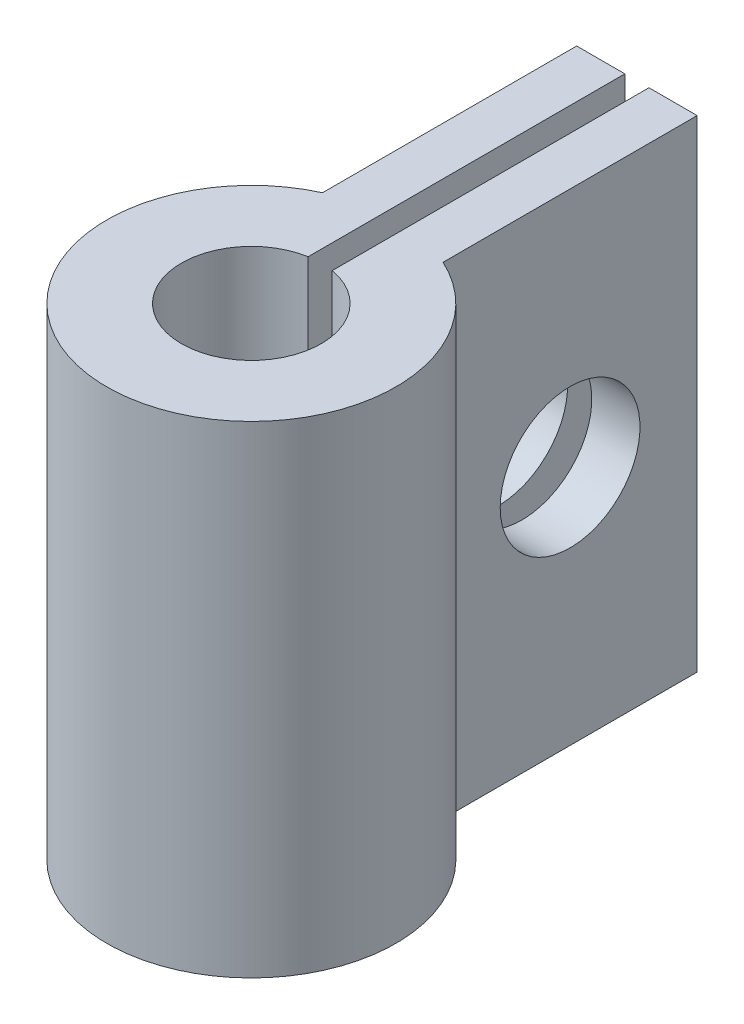
SolidWorks part; units mm, degrees
ref_plane "Front Plane" through (0, 0, 0) normal (0, 0, 1) x (1, 0, 0)
ref_plane "Top Plane" through (0, 0, 0) normal (0, 1, 0) x (1, 0, 0)
ref_plane "Right Plane" through (0, 0, 0) normal (1, 0, 0) x (0, 0, -1)
sketch "Sketch1" plane through (0, 0, 0) normal (0, 1, 0) x (1, 0, 0)
  circle A1 centre (0, 0) radius 6
extrude "Boss-Extrude1" add sketch "Sketch1" along normal blind 20 contours A1
sketch "Sketch3" plane through (0, 20, 0) normal (0, 1, 0) x (1, 0, 0)
  circle A0 centre (0, 0) radius 2.9
extrude "Cut-Extrude1" cut sketch "Sketch3" against normal blind 26
ref_plane "Plane1" through (2.5, 0, 0) normal (1, 0, 0) x (0, 0, -1)
ref_plane "Plane2" through (-2.5, 0, 0) normal (1, 0, 0) x (0, 0, -1)
sketch "Sketch4" plane through (-2.5, 0, 0) normal (1, 0, 0) x (0, 0, -1)
  line L0 (6, 20) -> (16, 20)
  line L1 (16, 20) -> (16, 0)
  line L2 (16, 0) -> (6, 0)
  line L3 (6, 0) -> (4.5452, 0)
  line L4 (-6, 0) -> (6, 0) construction
  line L5 (4.5452, 0) -> (4.5452, 20)
  line L6 (6, 20) -> (-6, 20) construction
  line L7 (4.5452, 20) -> (6, 20)
extrude "Boss-Extrude2" add sketch "Sketch4" along normal blind 2
sketch "Sketch5" plane through (2.5, 0, 0) normal (1, 0, 0) x (0, 0, -1)
  line L0 (6, 20) -> (16, 20)
  line L1 (16, 20) -> (16, 0)
  line L2 (16, 0) -> (6, 0)
  line L3 (6, 0) -> (4.2113, 0)
  line L4 (-6, 0) -> (6, 0) construction
  line L5 (4.2113, 0) -> (4.2113, 20)
  line L6 (6, 20) -> (-6, 20) construction
  line L7 (4.2113, 20) -> (6, 20)
extrude "Boss-Extrude3" add sketch "Sketch5" against normal blind 2
sketch "Sketch6" plane through (0, 0, -16) normal (0, 0, -1) x (-1, 0, 0)
  line L0 (-0.5, 20) -> (0.5, 20)
  line L1 (0.5, 20) -> (0.5, 0)
  line L2 (0.5, 0) -> (-0.5, 0)
  line L3 (-0.5, 0) -> (-0.5, 20)
extrude "Cut-Extrude2" cut sketch "Sketch6" against normal blind 17
sketch "Sketch7" plane through (-2.5, 0, 0) normal (-1, 0, 0) x (0, 0, 1)
  circle A0 centre (-10.7272, 10) radius 2.9
extrude "Cut-Extrude3" cut sketch "Sketch7" against normal blind 17
